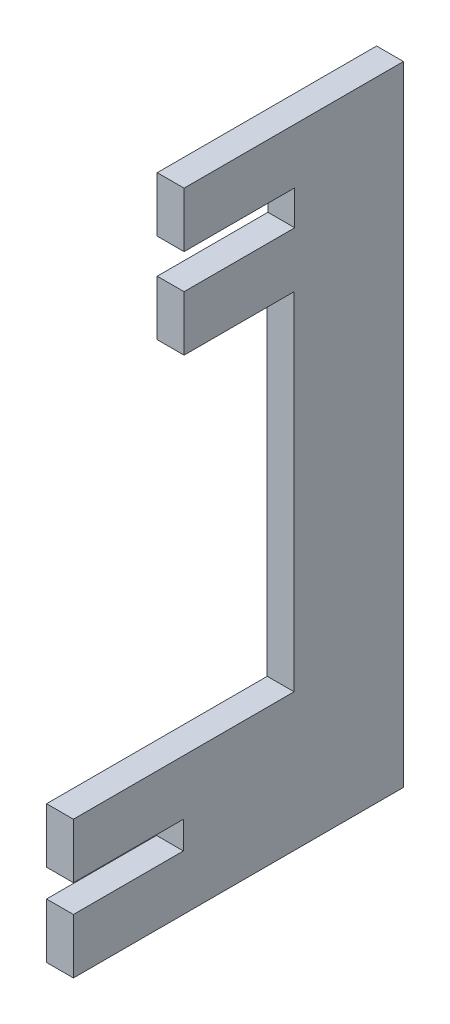
SolidWorks part; units mm, degrees
material "Corrugated Paper"
ref_plane "Front Plane" through (0, 0, 0) normal (0, 0, 1) x (1, 0, 0)
ref_plane "Top Plane" through (0, 0, 0) normal (0, 1, 0) x (1, 0, 0)
ref_plane "Right Plane" through (0, 0, 0) normal (1, 0, 0) x (0, 0, -1)
sketch "Sketch1" plane through (0, 0, 0) normal (1, 0, 0) x (0, 0, -1)
  line L0 (-12.7, -1.5875) -> (-12.7, -7.9375)
  line L1 (-12.7, 1.5875) -> (0, 1.5875)
  line L3 (-12.7, -1.5875) -> (0, -1.5875)
  line L4 (0, 1.5875) -> (0, -1.5875)
  line L5 (-12.7, -7.9375) -> (25.4, -7.9375)
  line L6 (-12.7, 1.5875) -> (-12.7, 7.9375)
  line L7 (-12.7, 7.9375) -> (12.7762, 7.9375)
  line L8 (25.4, -7.9375) -> (25.4, 64.6375)
  line L9 (12.7762, 7.9375) -> (12.7762, 47.9375)
  line L10 (12.7762, 47.9375) -> (0.0762, 47.9375)
  line L11 (25.4, 64.6375) -> (0.0762, 64.6375)
  line L12 (0.0762, 64.6375) -> (0.0762, 58.2875)
  line L13 (0.0762, 58.2875) -> (12.8524, 58.2875)
  line L14 (12.8524, 58.2875) -> (12.8524, 54.2875)
  line L15 (12.8524, 54.2875) -> (0.0762, 54.2875)
  line L16 (0.0762, 54.2875) -> (0.0762, 47.9375)
  line L17 (12.7762, 58.2875) -> (12.7762, 54.2875) construction
  dimension "D1" = 3.175
  dimension "D2" = 12.7
  dimension "D3" = 25.4
  dimension "D4" = 6.35
  dimension "D5" = 6.35
  dimension "D6" = 12.7762
  dimension "D7" = 40
  dimension "D8" = 4
  dimension "D9" = 12.7
  dimension "D10" = 6.35
  dimension "D11" = 0.0762
extrude "Boss-Extrude1" add sketch "Sketch1" along normal blind 3.0988
equation "\"rodThick\"= 0.085in"
equation "\"thick\"= 0.122in"
equation "\"clear\"= 0.003in"
equation "\"D1@Sketch1\"=\"thick\"+\"clear\""
equation "\"D6@Sketch1\"= 0.5 + \"clear\""
equation "\"D1@Boss-Extrude1\"=\"thick\""
equation "\"D11@Sketch1\"=\"clear\""
